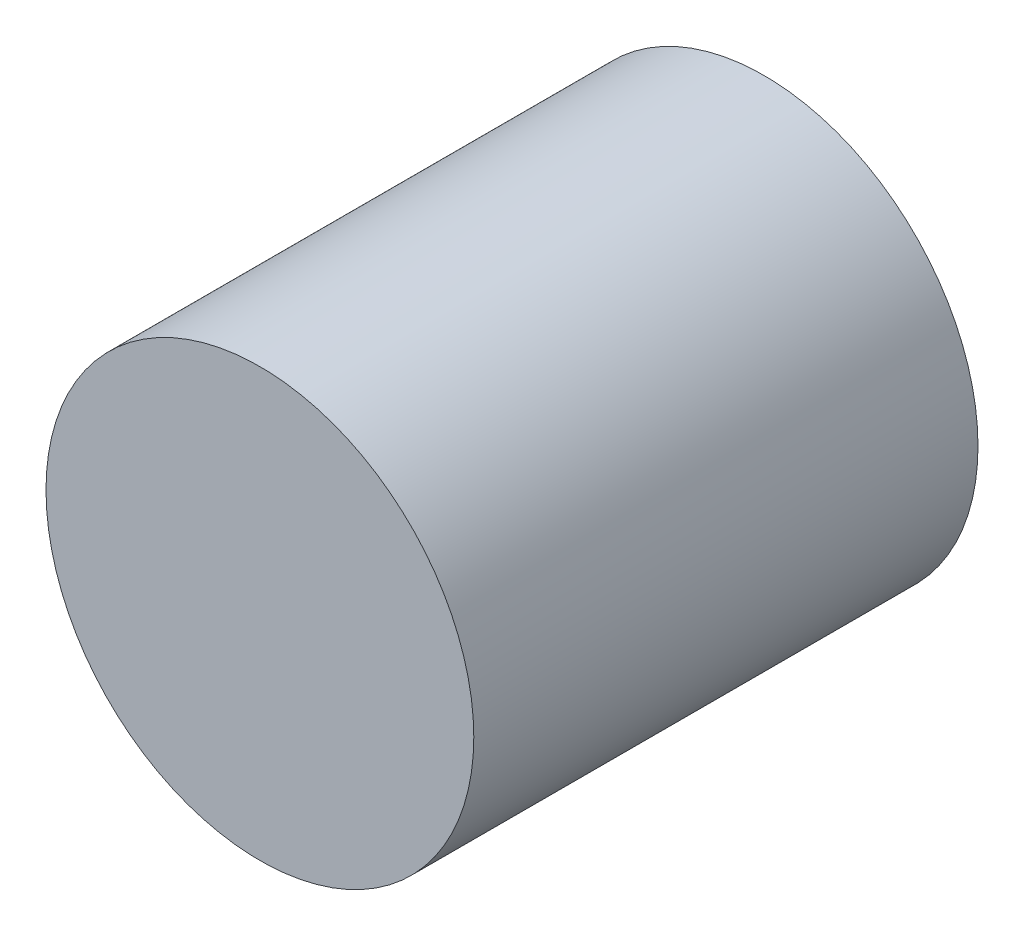
SolidWorks part; units mm, degrees
ref_plane "Front Plane" through (0, 0, 0) normal (0, 0, 1) x (1, 0, 0)
ref_plane "Top Plane" through (0, 0, 0) normal (0, 1, 0) x (1, 0, 0)
ref_plane "Right Plane" through (0, 0, 0) normal (1, 0, 0) x (0, 0, -1)
sketch "Sketch1" plane through (0, 0, 0) normal (0, 0, 1) x (1, 0, 0)
  circle A0 centre (0, 0) radius 14
  dimension "D1" = 28
extrude "Boss-Extrude1" add sketch "Sketch1" along normal blind 33
